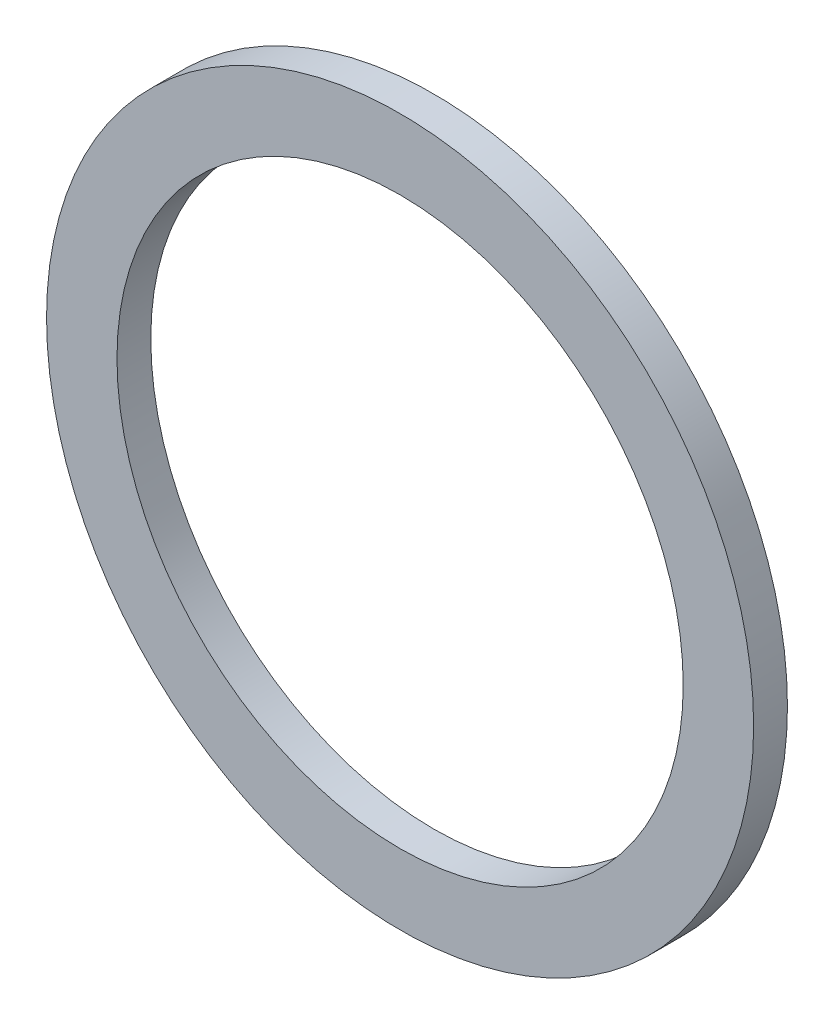
SolidWorks part; units mm, degrees
material "AISI 1020"
ref_plane "Front Plane" through (0, 0, 0) normal (0, 0, 1) x (1, 0, 0)
ref_plane "Top Plane" through (0, 0, 0) normal (0, 1, 0) x (1, 0, 0)
ref_plane "Right Plane" through (0, 0, 0) normal (1, 0, 0) x (0, 0, -1)
sketch "Sketch1" plane through (0, 0, 0) normal (0, 0, 1) x (1, 0, 0)
  circle A0 centre (0, 0) radius 25.527
  circle A1 centre (0, 0) radius 25.4 construction
  circle A2 centre (0, 0) radius 31.877
  dimension "D1" = 0.127
  dimension "D2" = 6.35
extrude "Boss-Extrude1" add sketch "Sketch1" along normal blind 3.048 contours A0 | A2
